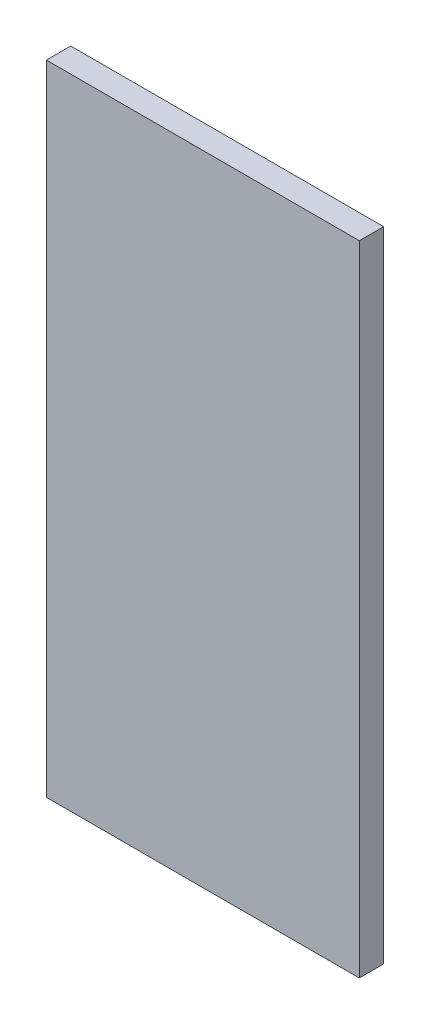
SolidWorks part; units mm, degrees
ref_plane "Front Plane" through (0, 0, 0) normal (0, 0, 1) x (1, 0, 0)
ref_plane "Top Plane" through (0, 0, 0) normal (0, 1, 0) x (1, 0, 0)
ref_plane "Right Plane" through (0, 0, 0) normal (1, 0, 0) x (0, 0, -1)
sketch "Sketch1" plane through (0, 0, 0) normal (0, 0, 1) x (1, 0, 0)
  line L1 (-245.05, 250) -> (0, 250)
  line L2 (-245.05, 250) -> (-245.05, -250)
  line L3 (-245.05, -250) -> (0, -250)
  line L4 (0, 250) -> (0, -250)
  dimension "D1" = 500
  dimension "D2" = 245.05
extrude "Boss-Extrude1" add sketch "Sketch1" along normal blind 19.05
